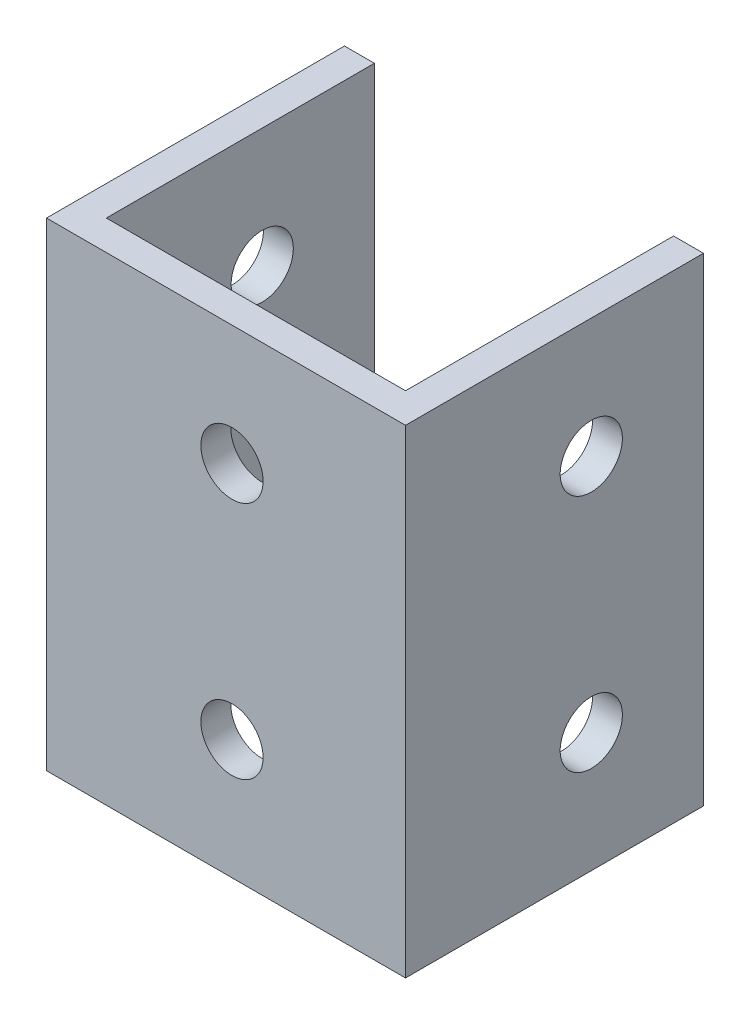
SolidWorks part; units mm, degrees
material "6061 Alloy"
ref_plane "Front Plane" through (0, 0, 0) normal (0, 0, 1) x (1, 0, 0)
ref_plane "Top Plane" through (0, 0, 0) normal (0, 1, 0) x (1, 0, 0)
ref_plane "Right Plane" through (0, 0, 0) normal (1, 0, 0) x (0, 0, -1)
sketch "Sketch2" plane through (0, 0, 0) normal (0, 1, 0) x (1, 0, 0)
  line L0 (0, 0) -> (0, -31.623)
  line L1 (0, -31.623) -> (38.1, -31.623)
  line L2 (38.1, -31.623) -> (38.1, 0)
  line L3 (38.1, 0) -> (34.925, 0)
  line L4 (34.925, 0) -> (34.925, -28.448)
  line L5 (34.925, -28.448) -> (3.175, -28.448)
  line L6 (3.175, -28.448) -> (3.175, 0)
  line L7 (3.175, 0) -> (0, 0)
  dimension "D1" = 31.623
  dimension "D2" = 38.1
  dimension "D3" = 3.175
  dimension "D4" = 3.175
  dimension "D5" = 3.175
extrude "Boss-Extrude1" add sketch "Sketch2" along normal blind 50.8
sketch "Sketch3" plane through (0, 0, 28.448) normal (0, 0, -1) x (-1, 0, 0)
  line L0 (-34.925, 0) -> (-3.175, 0) construction
  line L1 (-34.925, 50.8) -> (-34.925, 0) construction
  line L2 (-19.685, 0) -> (-19.685, 50.8) construction
  line L3 (-34.925, 50.8) -> (-3.175, 50.8) construction
  circle A0 centre (-19.685, 12.7) radius 3.302
  circle A1 centre (-19.685, 38.0911) radius 3.302
  dimension "D1" = 6.604
  dimension "D4" = 6.604
  dimension "D2" = 12.7
  dimension "D3" = 15.24
  dimension "D5" = 12.7089
  dimension "D6" = 15.24
extrude "Cut-Extrude1" cut sketch "Sketch3" against normal blind 50.8
sketch "Sketch4" plane through (38.1, 0, 0) normal (1, 0, 0) x (0, 0, -1)
  line L0 (-31.623, 50.8) -> (0, 50.8) construction
  line L3 (-31.623, 0) -> (0, 0) construction
  line L4 (0, 50.8) -> (0, 0) construction
  line L5 (0, 50.8) -> (0, 0) construction
  circle A0 centre (-11.9062, 38.1) radius 3.302
  circle A1 centre (-11.9062, 12.7) radius 3.302
  dimension "D1" = 6.604
  dimension "D2" = 12.7
  dimension "D3" = 12.7
  dimension "D4" = 11.9062
  dimension "D5" = 11.9062
extrude "Cut-Extrude2" cut sketch "Sketch4" against normal through all
